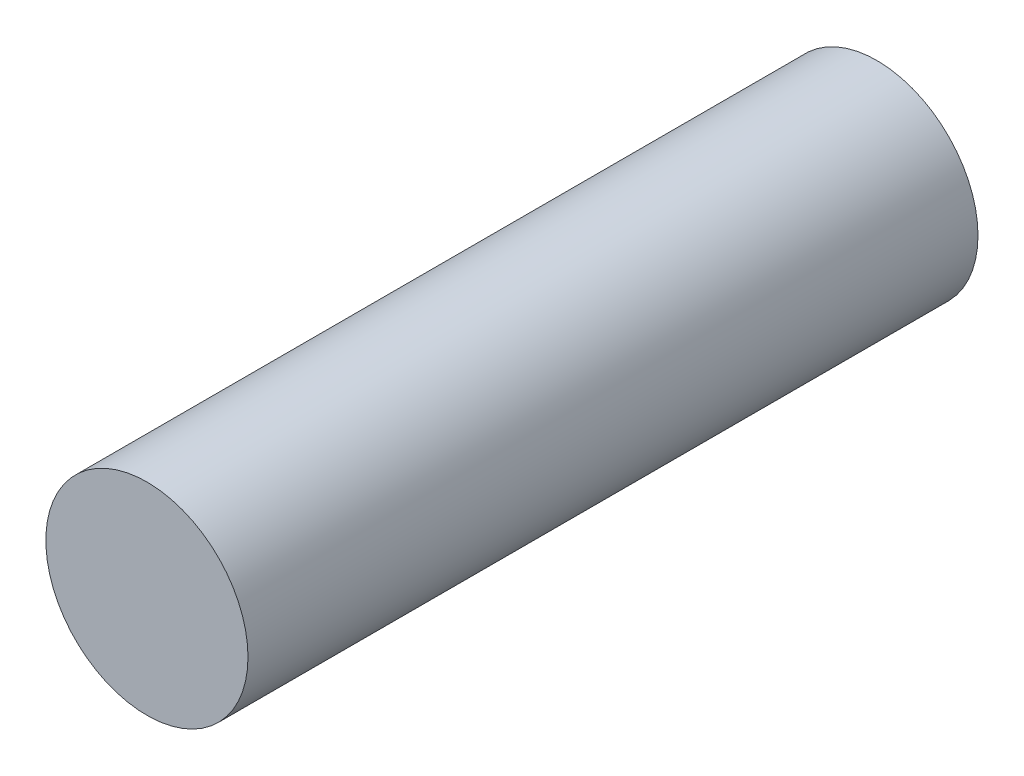
SolidWorks part; units mm, degrees
ref_plane "Front Plane" through (0, 0, 0) normal (0, 0, 1) x (1, 0, 0)
ref_plane "Top Plane" through (0, 0, 0) normal (0, 1, 0) x (1, 0, 0)
ref_plane "Right Plane" through (0, 0, 0) normal (1, 0, 0) x (0, 0, -1)
sketch "Sketch1" plane through (0, 0, 0) normal (0, 0, 1) x (1, 0, 0)
  circle A0 centre (0, 0) radius 9
  dimension "D1" = 18
extrude "Boss-Extrude1" add sketch "Sketch1" along normal blind 65 contours A0
